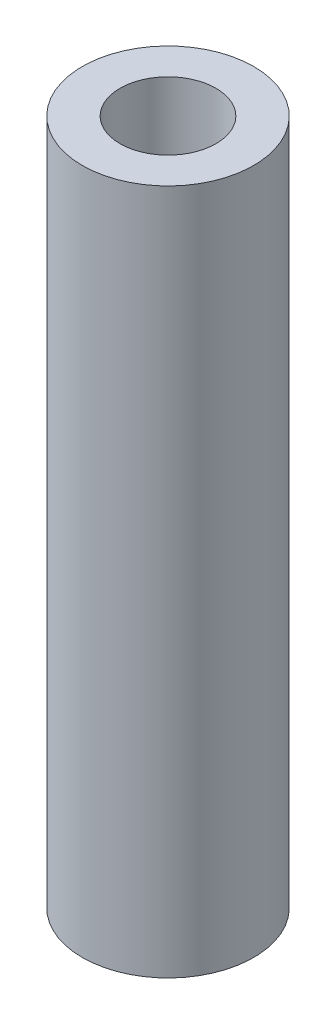
SolidWorks part; units mm, degrees
ref_plane "Front Plane" through (0, 0, 0) normal (0, 0, 1) x (1, 0, 0)
ref_plane "Top Plane" through (0, 0, 0) normal (0, 1, 0) x (1, 0, 0)
ref_plane "Right Plane" through (0, 0, 0) normal (1, 0, 0) x (0, 0, -1)
sketch "Sketch1" plane through (0, 0, 0) normal (0, 1, 0) x (1, 0, 0)
  circle A0 centre (0, 0) radius 1.778
  circle A1 centre (0, 0) radius 3.175
  dimension "D1" = 3.556
  dimension "D2" = 6.35
extrude "Boss-Extrude1" add sketch "Sketch1" along normal blind 25.4
